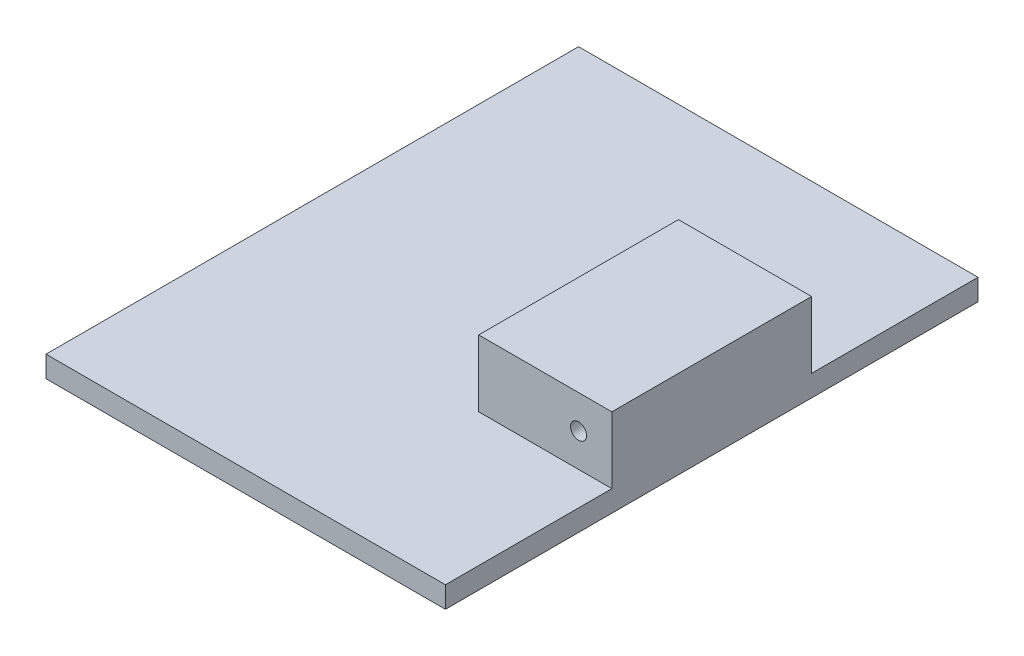
SolidWorks part; units mm, degrees
ref_plane "Front Plane" through (0, 0, 0) normal (0, 0, 1) x (1, 0, 0)
ref_plane "Top Plane" through (0, 0, 0) normal (0, 1, 0) x (1, 0, 0)
ref_plane "Right Plane" through (0, 0, 0) normal (1, 0, 0) x (0, 0, -1)
sketch "Sketch1" plane through (0, 0, 0) normal (0, 1, 0) x (1, 0, 0)
  line L1 (-150, -200) -> (150, -200)
  line L2 (-150, -200) -> (-150, 200)
  line L3 (-150, 200) -> (150, 200)
  line L4 (150, -200) -> (150, 200)
  line L5 (-150, -200) -> (150, 200) construction
  line L6 (-150, 200) -> (150, -200) construction
  point P0 (0, 0)
  dimension "D1" = 400
  dimension "D2" = 300
extrude "Boss-Extrude1" add sketch "Sketch1" along normal blind 16 contours L2 L3 L4 L1
sketch "Sketch2" plane through (0, 16, 0) normal (0, 1, 0) x (1, 0, 0)
  line L0 (-150, 0) -> (100, 0) construction
  line L1 (-150, -200) -> (-150, 200) construction
  line L2 (150, -200) -> (150, 200) construction
  line L3 (50, 75) -> (150, 75)
  line L4 (50, 75) -> (50, -75)
  line L5 (50, -75) -> (150, -75)
  line L6 (150, 75) -> (150, -75)
  line L7 (50, 75) -> (150, -75) construction
  line L8 (50, -75) -> (150, 75) construction
  point P9 (150, 0)
  dimension "D1" = 100
  dimension "D2" = 150
extrude "Boss-Extrude2" add sketch "Sketch2" along normal blind 50
sketch "Sketch3" plane through (0, 0, -75) normal (0, 0, -1) x (-1, 0, 0)
  line L0 (-50, 66) -> (-50, 16) construction
  line L1 (-150, 66) -> (-150, 16) construction
  circle A0 centre (-125, 41) radius 6
  point P3 (-50, 41)
  dimension "D1" = 25
extrude "Cut-Extrude1" cut sketch "Sketch3" against normal through all both and the other way through all
